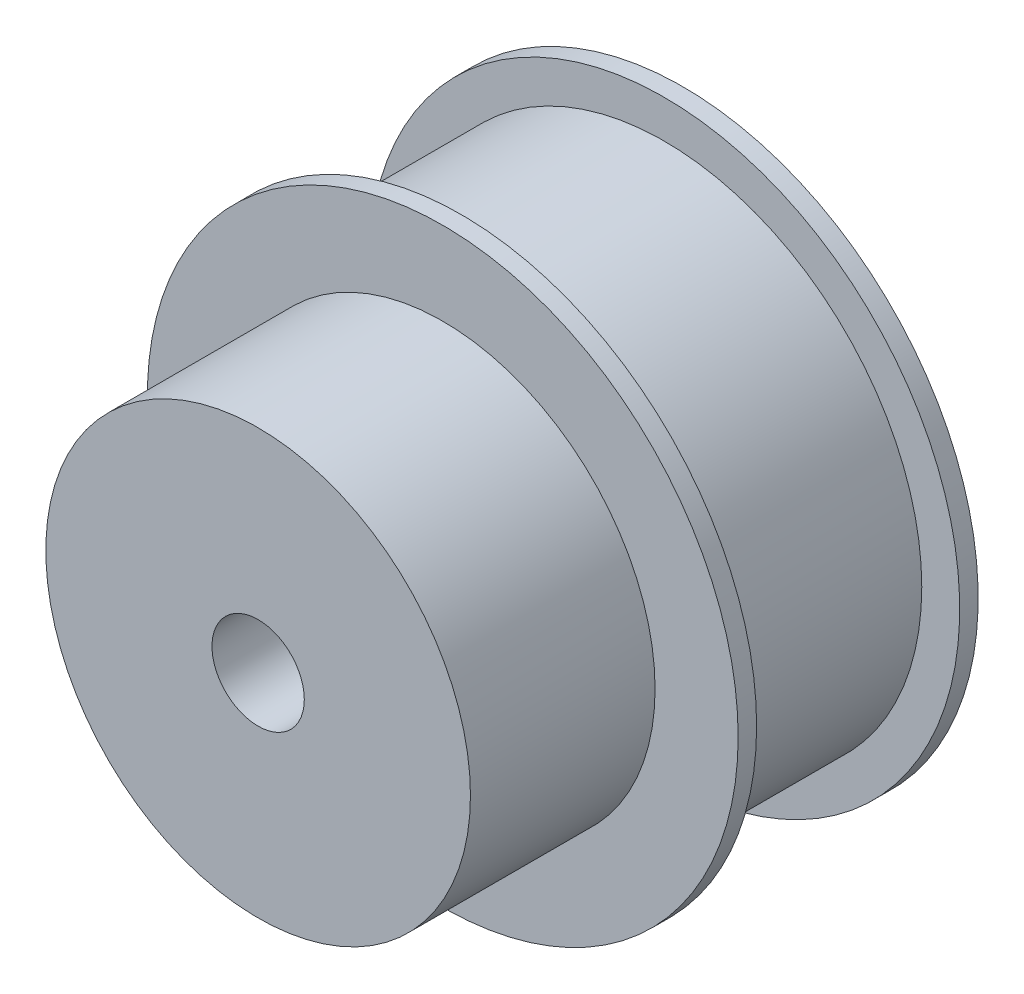
SolidWorks part; units mm, degrees
ref_plane "前视基准面" through (0, 0, 0) normal (0, 0, 1) x (1, 0, 0)
ref_plane "上视基准面" through (0, 0, 0) normal (0, 1, 0) x (1, 0, 0)
ref_plane "右视基准面" through (0, 0, 0) normal (1, 0, 0) x (0, 0, -1)
other "Configuration Table"
sketch "草图1" plane through (0, 0, 0) normal (0, 0, 1) x (1, 0, 0)
  circle A0 centre (0, 0) radius 11.5
  dimension "D1" = 23
extrude "凸台-拉伸1" add sketch "草图1" against normal blind 10
sketch "草图2" plane through (0, 0, -10) normal (0, 0, -1) x (-1, 0, 0)
  circle A0 centre (0, 0) radius 13.945
  dimension "D1" = 27.89
extrude "凸台-拉伸2" add sketch "草图2" along normal blind 13
sketch "草图3" plane through (0, 0, -23) normal (0, 0, -1) x (-1, 0, 0)
  circle A0 centre (0, 0) radius 16
  dimension "D1" = 32
extrude "凸台-拉伸3" add sketch "草图3" against normal blind 1
sketch "草图4" plane through (0, 0, -10) normal (0, 0, 1) x (1, 0, 0)
  circle A0 centre (0, 0) radius 16
  dimension "D1" = 32
extrude "凸台-拉伸4" add sketch "草图4" against normal blind 1
sketch "草图5" plane through (0, 0, 0) normal (0, 0, 1) x (1, 0, 0)
  circle A0 centre (0, 0) radius 2.5
  dimension "D1" = 5
extrude "切除-拉伸1" cut sketch "草图5" against normal through all both
